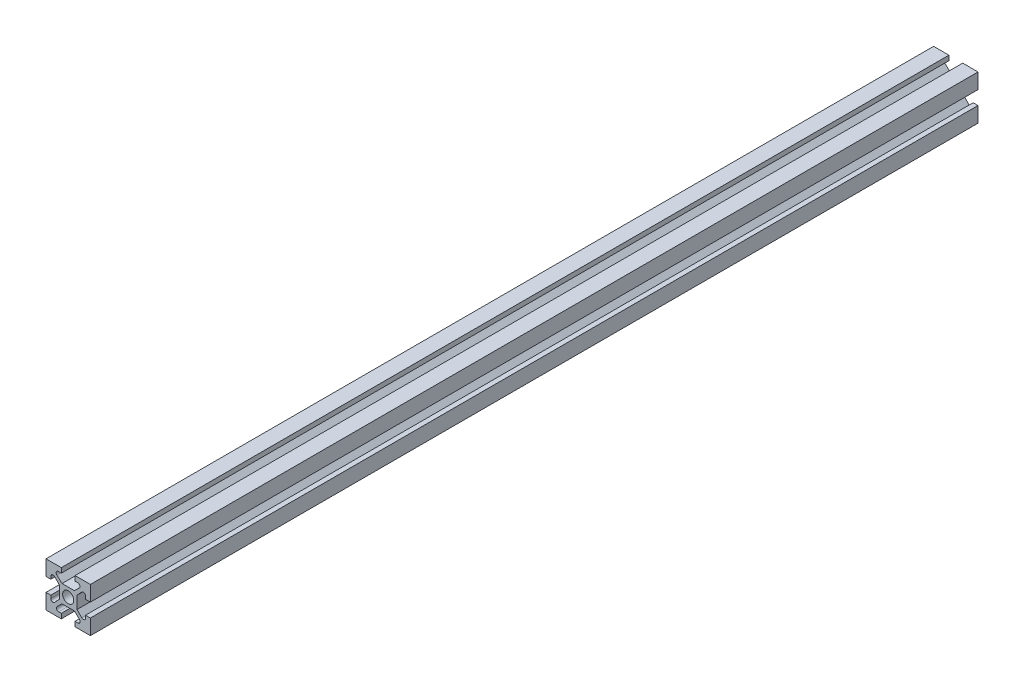
SolidWorks part; units mm, degrees
ref_plane "Front Plane" through (0, 0, 0) normal (0, 0, 1) x (1, 0, 0)
ref_plane "Top Plane" through (0, 0, 0) normal (0, 1, 0) x (1, 0, 0)
ref_plane "Right Plane" through (0, 0, 0) normal (1, 0, 0) x (0, 0, -1)
sketch "Sketch2" plane through (0, 0, 0) normal (0, 0, 1) x (1, 0, 0)
  line L0 (-295.6365, 99.3001) -> (355.6968, 99.3001) construction
  line L1 (53, 177) -> (305, 177) construction
  line L2 (0, 9.9554) -> (0, -10.0446) construction
  line L7 (-10, -10) -> (-3.1, -10)
  line L8 (-10, -10) -> (-10, -3.1)
  line L9 (-10, 10) -> (-3.1, 10)
  line L10 (10, -10) -> (10, -3.1)
  line L11 (-10, -10) -> (10, 10) construction
  line L12 (-10, 10) -> (10, -10) construction
  line L13 (-10, 0) -> (10, 0) construction
  line L14 (-10, 3.1) -> (-7.8186, 3.1)
  line L15 (-7.8186, 3.1) -> (-7.8186, 4.2854)
  line L16 (-6.1072, 4.9882) -> (-3.9647, 2.8197)
  line L17 (-3.9647, 2.8197) -> (-3.9647, 0)
  line L18 (-3.1, 10) -> (-3.1, 7.839)
  line L19 (-3.1, 7.839) -> (-4.4279, 7.839)
  line L20 (-5.1052, 6.1033) -> (-2.7827, 3.9647)
  line L21 (-2.7827, 3.9647) -> (0, 3.9647)
  line L22 (3.1, 10) -> (3.1, 7.8186)
  line L23 (3.1, 7.8186) -> (4.2854, 7.8186)
  line L24 (4.9882, 6.1072) -> (2.8197, 3.9647)
  line L25 (2.8197, 3.9647) -> (0, 3.9647)
  line L26 (6.1033, 5.1052) -> (3.9647, 2.7827)
  line L27 (3.9647, 2.7827) -> (3.9647, 0)
  line L28 (7.839, 3.1) -> (7.839, 4.4279)
  line L29 (10, 3.1) -> (7.839, 3.1)
  line L30 (10, -3.1) -> (7.8186, -3.1)
  line L31 (7.8186, -3.1) -> (7.8186, -4.2854)
  line L32 (6.1072, -4.9882) -> (3.9647, -2.8197)
  line L33 (3.9647, -2.8197) -> (3.9647, 0)
  line L34 (5.1052, -6.1033) -> (2.7827, -3.9647)
  line L35 (2.7827, -3.9647) -> (0, -3.9647)
  line L36 (3.1, -7.839) -> (4.4279, -7.839)
  line L37 (3.1, -10) -> (3.1, -7.839)
  line L38 (-3.1, -10) -> (-3.1, -7.8186)
  line L39 (-3.1, -7.8186) -> (-4.2854, -7.8186)
  line L40 (-4.9882, -6.1072) -> (-2.8197, -3.9647)
  line L41 (-2.8197, -3.9647) -> (0, -3.9647)
  line L42 (-6.1033, -5.1052) -> (-3.9647, -2.7827)
  line L43 (-3.9647, -2.7827) -> (-3.9647, 0)
  line L44 (-7.839, -3.1) -> (-7.839, -4.4279)
  line L45 (-10, -3.1) -> (-7.839, -3.1)
  line L46 (3.1, 10) -> (10, 10)
  line L47 (10, 3.1) -> (10, 10)
  line L48 (3.1, -10) -> (10, -10)
  line L49 (-10, 3.1) -> (-10, 10)
  circle A1 centre (0, 0) radius 2.5
  arc A2 (-4.4279, 7.839) -> (-5.1052, 6.1033) centre (-4.4279, 6.839) ccw
  arc A3 (-7.8186, 4.2854) -> (-6.1072, 4.9882) centre (-6.8186, 4.2854) cw
  arc A4 (4.2854, 7.8186) -> (4.9882, 6.1072) centre (4.2854, 6.8186) cw
  arc A5 (7.839, 4.4279) -> (6.1033, 5.1052) centre (6.839, 4.4279) ccw
  arc A6 (7.8186, -4.2854) -> (6.1072, -4.9882) centre (6.8186, -4.2854) cw
  arc A7 (4.4279, -7.839) -> (5.1052, -6.1033) centre (4.4279, -6.839) ccw
  arc A8 (-4.2854, -7.8186) -> (-4.9882, -6.1072) centre (-4.2854, -6.8186) cw
  arc A9 (-7.839, -4.4279) -> (-6.1033, -5.1052) centre (-6.839, -4.4279) ccw
  dimension "D1" = 3.1
  dimension "D5" = 1
  dimension "D2" = 20
  dimension "D3" = 20
  dimension "D4" = 3.1
  dimension "D6" = 4
extrude "Boss-Extrude1" add sketch "Sketch2" along normal blind 400
